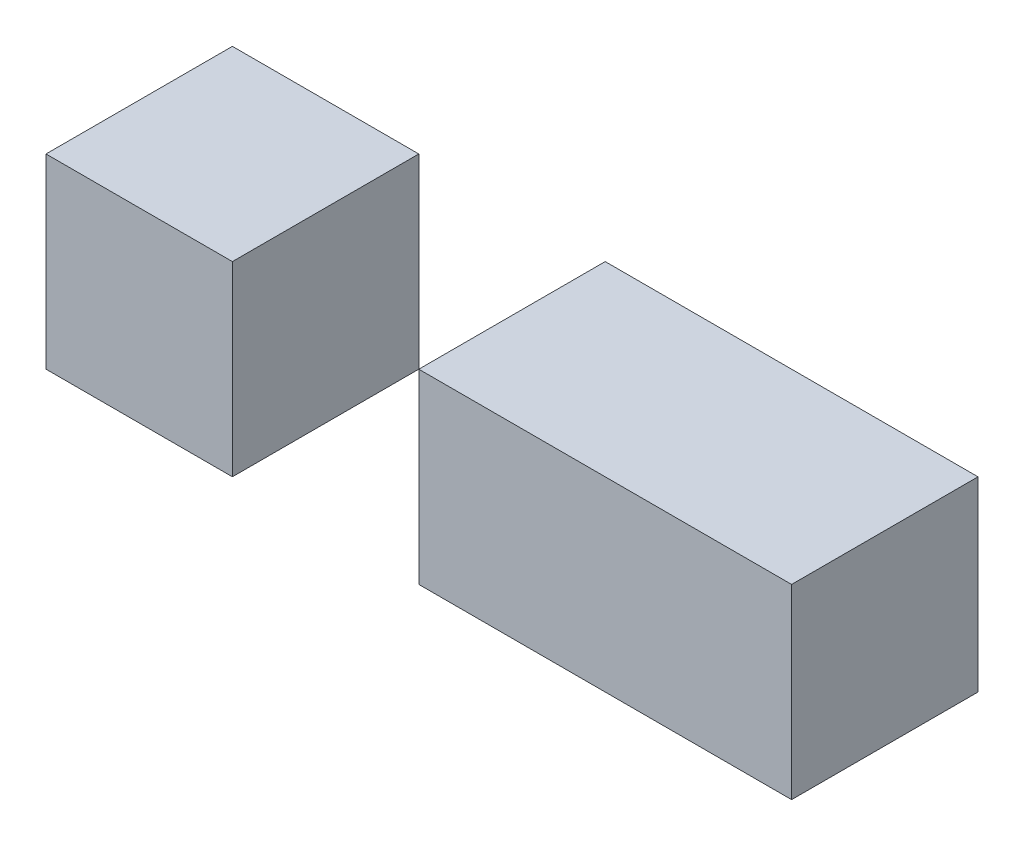
SolidWorks part; units mm, degrees
ref_plane "前视基准面" through (0, 0, 0) normal (0, 0, 1) x (1, 0, 0)
ref_plane "上视基准面" through (0, 0, 0) normal (0, 1, 0) x (1, 0, 0)
ref_plane "右视基准面" through (0, 0, 0) normal (1, 0, 0) x (0, 0, -1)
other "Configuration Table"
sketch "SelectionSeed" plane through (0, 0, 0) normal (0, 0, 1) x (1, 0, 0)
  line L1 (0, 0) -> (10, 0)
  line L2 (0, 0) -> (0, 10)
  line L3 (0, 10) -> (10, 10)
  line L4 (10, 0) -> (10, 10)
  line L6 (20, 0) -> (40, 0)
  line L7 (20, 0) -> (20, 10)
  line L8 (20, 10) -> (40, 10)
  line L9 (40, 0) -> (40, 10)
extrude "SelectionExtrude" add sketch "SelectionSeed" along normal blind 10 contours L6 L9 L8 L7 | L1 L4 L3 L2
